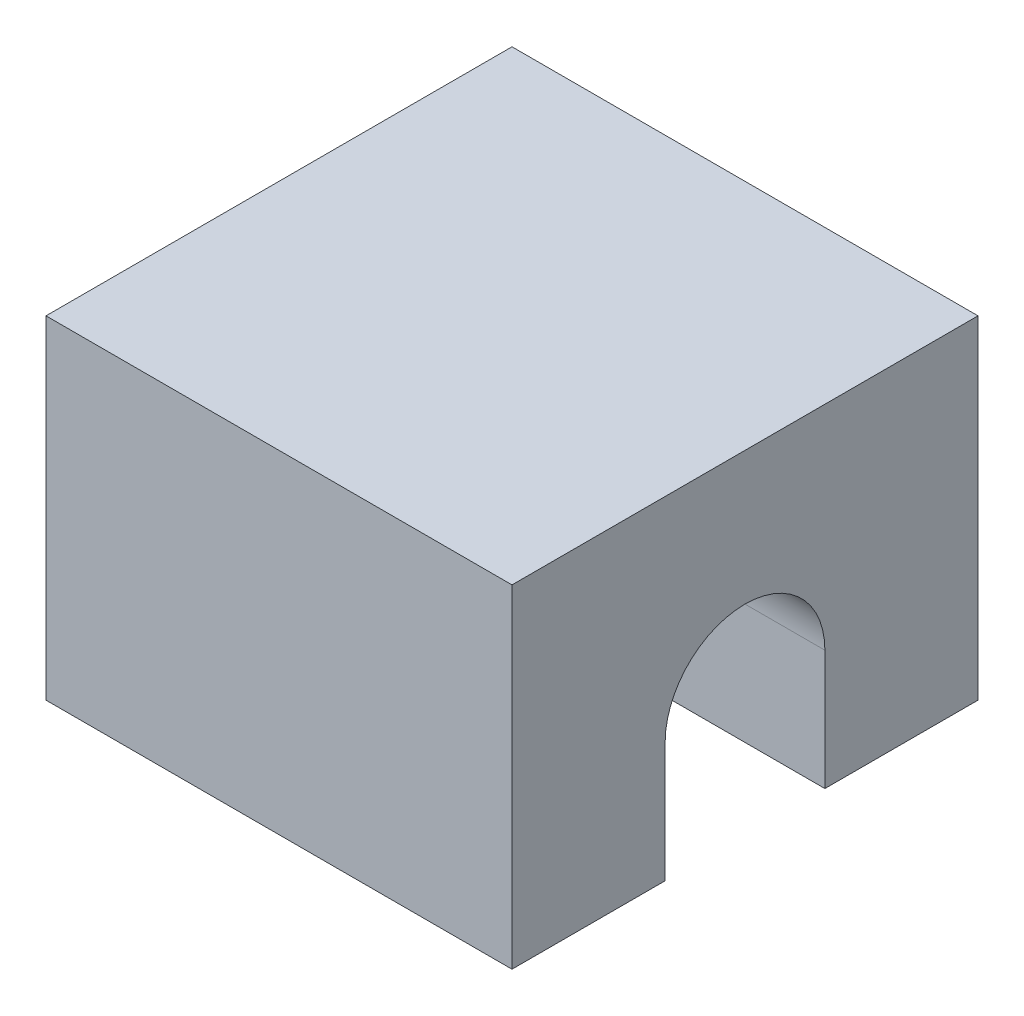
SolidWorks part; units mm, degrees
ref_plane "Front Plane" through (0, 0, 0) normal (0, 0, 1) x (1, 0, 0)
ref_plane "Top Plane" through (0, 0, 0) normal (0, 1, 0) x (1, 0, 0)
ref_plane "Right Plane" through (0, 0, 0) normal (1, 0, 0) x (0, 0, -1)
sketch "Sketch1" plane through (0, 0, 0) normal (1, 0, 0) x (0, 0, -1)
  line L0 (-8.8218, 16.7816) -> (-8.8218, 6.7816)
  line L1 (-26.3218, 16.7816) -> (8.6782, 16.7816)
  line L2 (-26.3218, 16.7816) -> (-26.3218, -8.2184)
  line L3 (-26.3218, -8.2184) -> (-14.8218, -8.2184)
  line L4 (8.6782, 16.7816) -> (8.6782, -8.2184)
  line L5 (-2.8218, -8.2184) -> (8.6782, -8.2184)
  line L7 (-14.8218, 0.7816) -> (-14.8218, -8.2184)
  line L9 (-2.8218, 0.7816) -> (-2.8218, -8.2184)
  arc A0 (-2.8218, 0.7816) -> (-14.8218, 0.7816) centre (-8.8218, 0.7816) ccw
  dimension "D4" = 12
  dimension "D1" = 25
  dimension "D2" = 35
  dimension "D3" = 16
extrude "Boss-Extrude1" add sketch "Sketch1" along normal blind 35 contours A0 L0 L1 L2 L3 L7 | A0 L9 L5 L4 L1 L0
